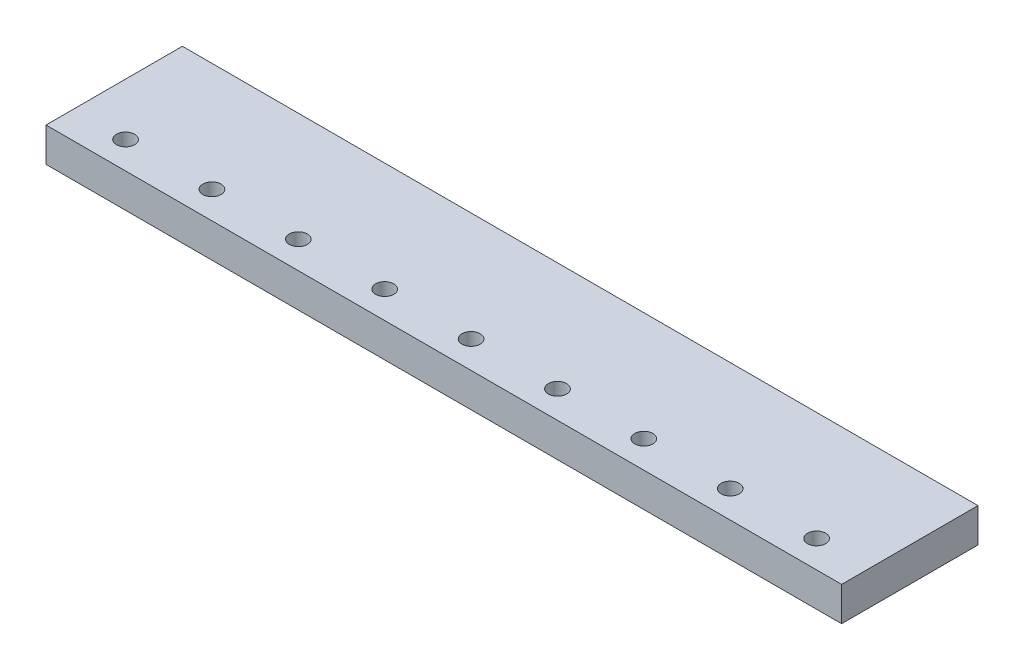
SolidWorks part; units mm, degrees
material "Maple"
ref_plane "Front Plane" through (0, 0, 0) normal (0, 0, 1) x (1, 0, 0)
ref_plane "Top Plane" through (0, 0, 0) normal (0, 1, 0) x (1, 0, 0)
ref_plane "Right Plane" through (0, 0, 0) normal (1, 0, 0) x (0, 0, -1)
sketch "Sketch1" plane through (0, 0, 0) normal (0, 1, 0) x (1, 0, 0)
  line L1 (0, 0) -> (350, 0)
  line L2 (0, 0) -> (0, -60)
  line L3 (0, -60) -> (350, -60)
  line L4 (350, 0) -> (350, -60)
  dimension "D1" = 350
  dimension "D2" = 60
extrude "Boss-Extrude1" add sketch "Sketch1" along normal blind 15
sketch "Sketch2" plane through (0, 15, 0) normal (0, 1, 0) x (1, 0, 0)
  line L0 (0, 0) -> (0, -60) construction
  line L2 (0, -60) -> (350, -60) construction
  line L3 (350, -60) -> (350, 0) construction
  circle A0 centre (23, -48) radius 4
  circle A1 centre (61, -48) radius 4
  circle A2 centre (99, -48) radius 4
  circle A3 centre (137, -48) radius 4
  circle A4 centre (175, -48) radius 4
  circle A5 centre (213, -48) radius 4
  circle A6 centre (251, -48) radius 4
  circle A7 centre (289, -48) radius 4
  circle A8 centre (327, -48) radius 4
  dimension "D2" = 8
  dimension "D1" = 23
  dimension "D3" = 12
  dimension "D5" = 23
  dimension "D4" = 9
extrude "Cut-Extrude1" cut sketch "Sketch2" against normal through all
